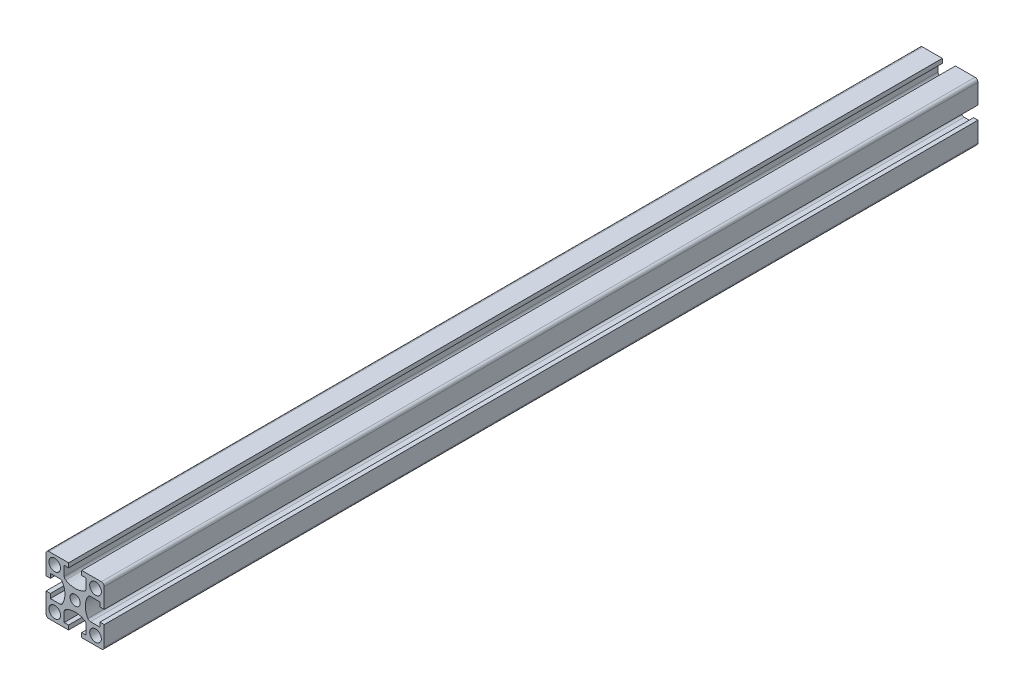
SolidWorks part; units mm, degrees
ref_plane "Front Plane" through (0, 0, 0) normal (0, 0, 1) x (1, 0, 0)
ref_plane "Top Plane" through (0, 0, 0) normal (0, 1, 0) x (1, 0, 0)
ref_plane "Right Plane" through (0, 0, 0) normal (1, 0, 0) x (0, 0, -1)
sketch "Sketch1" plane through (0, 0, 0) normal (0, 0, 1) x (1, 0, 0)
  line L64 (-20, 18) -> (-20, 4.5)
  line L65 (-20, 4.5) -> (-17, 4.5)
  line L66 (-17, 4.5) -> (-17, 7.5)
  line L67 (-17, 7.5) -> (-10.4737, 7.5)
  line L68 (-10.4737, -7.5) -> (-17, -7.5)
  line L69 (-17, -7.5) -> (-17, -4.5)
  line L70 (-17, -4.5) -> (-20, -4.5)
  line L71 (-20, -4.5) -> (-20, -18)
  line L72 (-18, -20) -> (-4.5, -20)
  line L73 (-4.5, -20) -> (-4.5, -17)
  line L74 (-4.5, -17) -> (-7.5, -17)
  line L75 (-7.5, -17) -> (-7.5, -10.4737)
  line L76 (7.5, -10.4737) -> (7.5, -17)
  line L77 (7.5, -17) -> (4.5, -17)
  line L78 (4.5, -17) -> (4.5, -20)
  line L79 (4.5, -20) -> (18, -20)
  line L80 (20, -18) -> (20, -4.5)
  line L81 (20, -4.5) -> (17, -4.5)
  line L82 (17, -4.5) -> (17, -7.5)
  line L83 (17, -7.5) -> (10.4737, -7.5)
  line L84 (10.4737, 7.5) -> (17, 7.5)
  line L85 (17, 7.5) -> (17, 4.5)
  line L86 (17, 4.5) -> (20, 4.5)
  line L87 (20, 4.5) -> (20, 18)
  line L88 (18, 20) -> (4.5, 20)
  line L89 (4.5, 20) -> (4.5, 17)
  line L90 (4.5, 17) -> (7.5, 17)
  line L91 (7.5, 17) -> (7.5, 10.4737)
  line L92 (-7.5, 10.4737) -> (-7.5, 17)
  line L93 (-7.5, 17) -> (-4.5, 17)
  line L94 (-4.5, 17) -> (-4.5, 20)
  line L95 (-4.5, 20) -> (-18, 20)
  circle A5 centre (-14, -14) radius 4
  circle A6 centre (14, -14) radius 4
  circle A7 centre (14, 14) radius 4
  circle A8 centre (0, 0) radius 3.5
  circle A9 centre (-14, 14) radius 4
  arc A32 (-18, 20) -> (-20, 18) centre (-18, 18) ccw
  arc A33 (-8.7417, 6.5) -> (-10.4737, 7.5) centre (-10.4737, 5.5) ccw
  arc A34 (-8.7417, -6.5) -> (-8.7417, 6.5) centre (-20, 0) ccw
  arc A35 (-10.4737, -7.5) -> (-8.7417, -6.5) centre (-10.4737, -5.5) ccw
  arc A36 (-20, -18) -> (-18, -20) centre (-18, -18) ccw
  arc A37 (-6.5, -8.7417) -> (-7.5, -10.4737) centre (-5.5, -10.4737) ccw
  arc A38 (6.5, -8.7417) -> (-6.5, -8.7417) centre (0, -20) ccw
  arc A39 (7.5, -10.4737) -> (6.5, -8.7417) centre (5.5, -10.4737) ccw
  arc A40 (18, -20) -> (20, -18) centre (18, -18) ccw
  arc A41 (8.7417, -6.5) -> (10.4737, -7.5) centre (10.4737, -5.5) ccw
  arc A42 (8.7417, 6.5) -> (8.7417, -6.5) centre (20, 0) ccw
  arc A43 (10.4737, 7.5) -> (8.7417, 6.5) centre (10.4737, 5.5) ccw
  arc A44 (20, 18) -> (18, 20) centre (18, 18) ccw
  arc A45 (6.5, 8.7417) -> (7.5, 10.4737) centre (5.5, 10.4737) ccw
  arc A46 (-6.5, 8.7417) -> (6.5, 8.7417) centre (0, 20) ccw
  arc A47 (-7.5, 10.4737) -> (-6.5, 8.7417) centre (-5.5, 10.4737) ccw
extrude "Boss-Extrude1" add sketch "Sketch1" along normal blind 600
